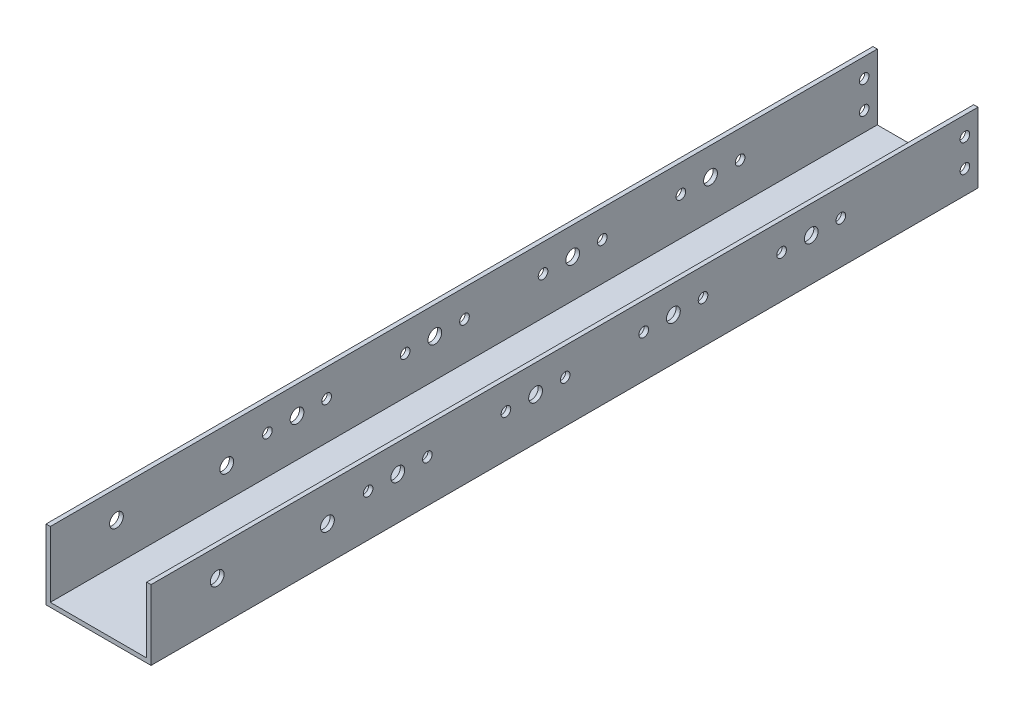
SolidWorks part; units mm, degrees
ref_plane "Front Plane" through (0, 0, 0) normal (0, 0, 1) x (1, 0, 0)
ref_plane "Top Plane" through (0, 0, 0) normal (0, 1, 0) x (1, 0, 0)
ref_plane "Right Plane" through (0, 0, 0) normal (1, 0, 0) x (0, 0, -1)
sketch "Sketch1" plane through (0, 0, 0) normal (0, 0, 1) x (1, 0, 0)
  line L0 (-19.05, 12.7) -> (-17.4875, 12.7)
  line L1 (-17.4875, 12.7) -> (-17.4875, -11.1375)
  line L2 (-17.4875, -11.1375) -> (17.4875, -11.1375)
  line L3 (17.4875, -11.1375) -> (17.4875, 12.7)
  line L4 (17.4875, 12.7) -> (19.05, 12.7)
  line L5 (19.05, 12.7) -> (19.05, -12.7)
  line L6 (19.05, -12.7) -> (-19.05, -12.7)
  line L7 (-19.05, -12.7) -> (-19.05, 12.7)
  line L8 (-17.4875, -11.1375) -> (-17.4875, -12.7) construction
  point P2 (0, -12.7)
  point P9 (-19.05, 0)
  dimension "D1" = 1.5625
  dimension "D2" = 38.1
  dimension "D3" = 25.4
extrude "Boss-Extrude1" add sketch "Sketch1" along normal mid plane 300
sketch "Sketch2" plane through (19.05, 0, 0) normal (1, 0, 0) x (0, 0, -1)
  line L1 (-71.25, 2.7) -> (-49.75, 2.7) construction
  line L2 (145.25, -4.2187) -> (145.25, 5.7813) construction
  line L4 (-150, -11.1375) -> (150, -11.1375) construction
  line L5 (-150, -11.1375) -> (150, -11.1375) construction
  line L6 (150, -12.7) -> (150, 12.7) construction
  line L7 (135, 12.7) -> (135, -11.1375) construction
  line L8 (-150, 12.7) -> (150, 12.7) construction
  circle A0 centre (145.25, 5.7813) radius 1.75
  circle A1 centre (145.25, -4.2187) radius 1.75
  circle A3 centre (-86, -0.1375) radius 2.5
  circle A4 centre (-126, 2.7) radius 2.5
  circle A5 centre (-60.5, 2.7) radius 2.5
  circle A11 centre (-71.25, 2.7) radius 1.75
  circle A12 centre (-49.75, 2.7) radius 1.75
  circle A13 centre (-21.25, 2.7) radius 1.75
  circle A14 centre (-10.5, 2.7) radius 2.5
  circle A15 centre (0.25, 2.7) radius 1.75
  circle A16 centre (28.75, 2.7) radius 1.75
  circle A17 centre (39.5, 2.7) radius 2.5
  circle A18 centre (50.25, 2.7) radius 1.75
  circle A19 centre (78.75, 2.7) radius 1.75
  circle A20 centre (89.5, 2.7) radius 2.5
  circle A21 centre (100.25, 2.7) radius 1.75
  circle A25 centre (-60.5, 2.7) radius 7 construction
  circle A26 centre (89.5, 2.7) radius 8 construction
  circle A27 centre (89.5, 2.7) radius 5 construction
  circle A28 centre (-86, -0.1375) radius 8 construction
  circle A30 centre (115, -0.1375) radius 8 construction
  circle A31 centre (115, -0.1375) radius 2.5 construction
  point P12 (-78, -0.1375)
  point P13 (107, -0.1375)
  point P14 (-73, 2.7)
  point P20 (145.25, 0.7813)
  point P21 (135, 0.7812)
  point P22 (147, 5.7812)
  point P55 (89.5, 7.7)
  point P57 (-67.5, 2.7)
  point P58 (-69.5, 2.7)
  point P59 (102, 2.7)
  point P67 (-86, -8.1375)
  dimension "D1" = 5
  dimension "D5" = 2
  dimension "D9" = 10
  dimension "D11" = 14
  dimension "D15" = 16
  dimension "D18" = 40
  dimension "D6" = 3.5
  dimension "D3" = 3
  dimension "D4" = 10
  dimension "D7" = 15
  dimension "D8" = 20
  dimension "D10" = 5
  dimension "D12" = 2
  dimension "D13" = 50
  dimension "D14" = 5
  dimension "D16" = 3
  dimension "D17" = 5
  dimension "D2" = 4
extrude "Cut-Extrude1" cut sketch "Sketch2" against normal through all
